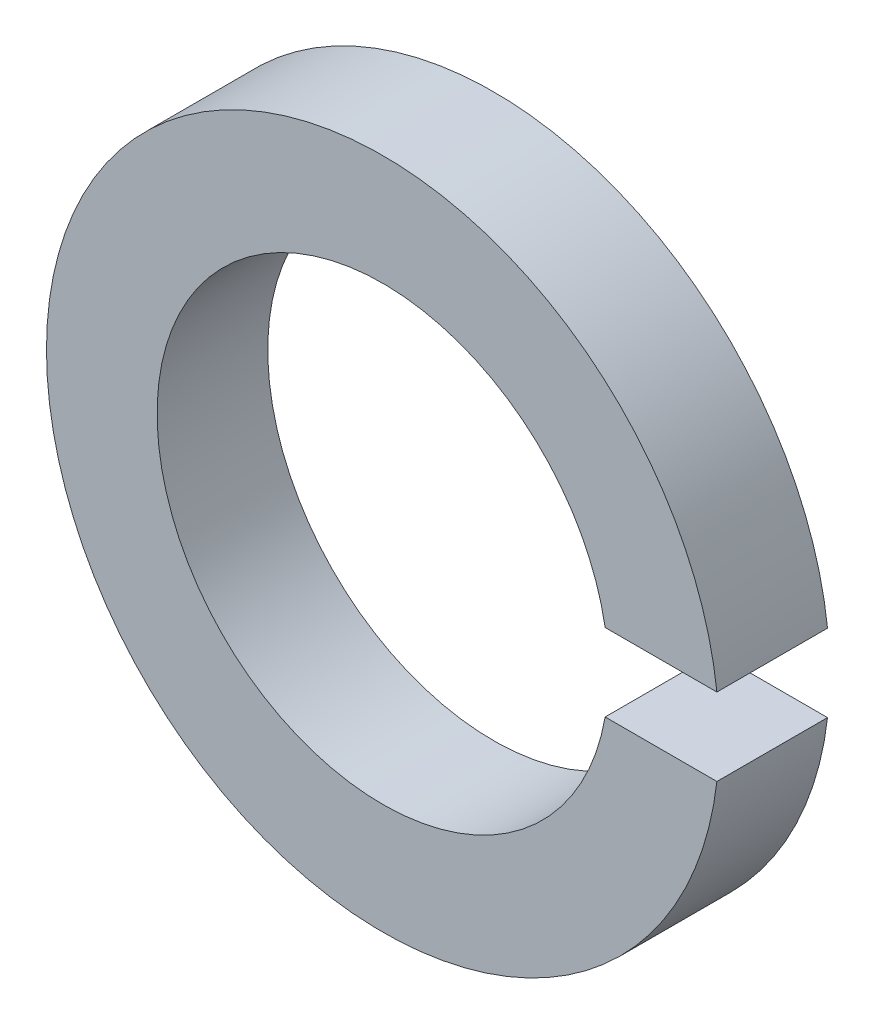
SolidWorks part; units mm, degrees
ref_plane "Спереди" through (0, 0, 0) normal (0, 0, 1) x (1, 0, 0)
ref_plane "Сверху" through (0, 0, 0) normal (0, 1, 0) x (1, 0, 0)
ref_plane "Справа" through (0, 0, 0) normal (1, 0, 0) x (0, 0, -1)
sketch "Эскиз1" plane through (0, 0, 0) normal (0, 0, 1) x (1, 0, 0)
  circle A0 centre (0, 0) radius 7.6
  circle A1 centre (0, 0) radius 5.1
  dimension "D1" = 15.2
  dimension "D2" = 10.2
extrude "Вытянуть1" add sketch "Эскиз1" along normal blind 2.5
sketch "Эскиз2" plane through (0, 0, 2.5) normal (0, 0, 1) x (1, 0, 0)
  line L0 (0, 0) -> (0.123, 0) construction
  line L1 (7.6, 0) -> (-7.6, 0) construction
  line L3 (4.9311, 0.875) -> (7.8366, 0.875)
  line L4 (4.9311, 0.875) -> (4.9311, -0.875)
  line L5 (4.9311, -0.875) -> (7.8366, -0.875)
  line L6 (7.8366, 0.875) -> (7.8366, -0.875)
  circle A0 centre (0, 0) radius 7.6 construction
  dimension "D1" = 0.875
  dimension "D2" = 1.75
extrude "Вырез-Вытянуть1" cut sketch "Эскиз2" against normal through all
